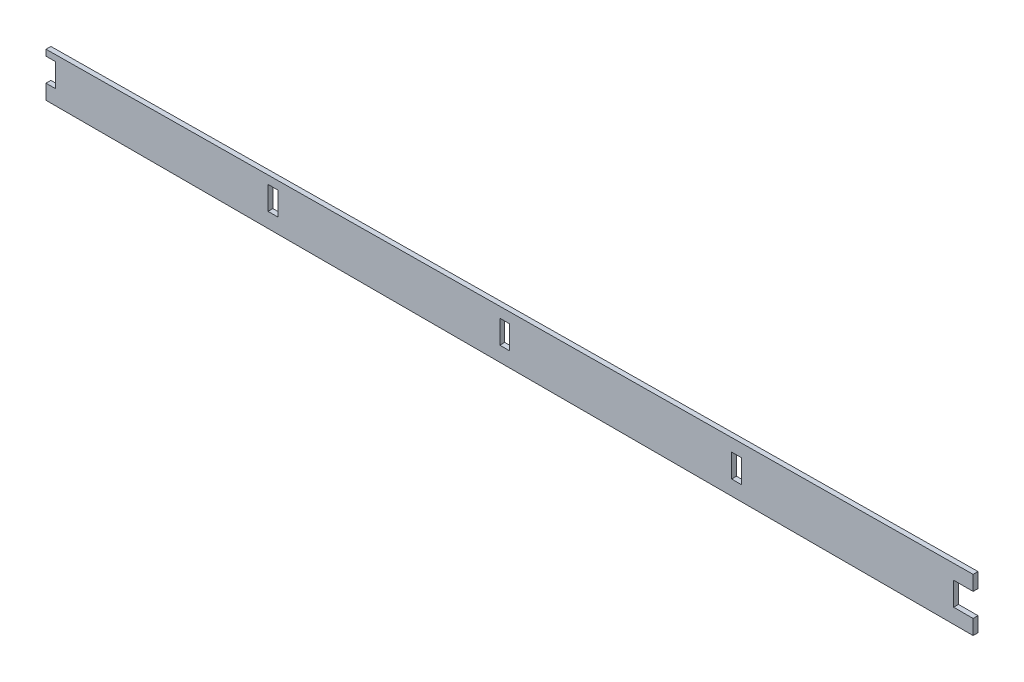
SolidWorks part; units mm, degrees
material "Balsa"
ref_plane "Front Plane" through (0, 0, 0) normal (0, 0, 1) x (1, 0, 0)
ref_plane "Top Plane" through (0, 0, 0) normal (0, 1, 0) x (1, 0, 0)
ref_plane "Right Plane" through (0, 0, 0) normal (1, 0, 0) x (0, 0, -1)
sketch "Sketch1" plane through (0, 0, 0) normal (0, 0, 1) x (1, 0, 0)
  line L0 (88.3257, 32.6276) -> (81.9757, 32.6276)
  line L1 (81.9757, 32.6276) -> (81.9757, 25.0076)
  line L2 (81.9757, 25.0076) -> (88.3257, 25.0076)
  line L3 (88.3257, 25.0076) -> (88.3257, 20.1687)
  line L4 (88.3257, 20.1687) -> (-213.9343, 20.1687)
  line L5 (-213.9343, 20.1687) -> (-213.9343, 25.0076)
  line L6 (-213.9343, 25.0076) -> (-210.7593, 25.0076)
  line L7 (-210.7593, 25.0076) -> (-210.7593, 32.6276)
  line L8 (-210.7593, 32.6276) -> (-213.9343, 32.6276)
  line L9 (-213.9343, 32.6276) -> (-213.9343, 34.5959)
  line L10 (-213.9343, 34.5959) -> (-210.7593, 34.6261) construction
  line L11 (-213.9343, 34.5959) -> (88.3257, 37.4665)
  line L12 (88.3257, 37.4665) -> (88.3257, 32.6276)
  line L13 (-138.3693, 25.0076) -> (-141.5443, 25.0076)
  line L14 (-141.5443, 25.0076) -> (-141.5443, 32.6276)
  line L15 (-141.5443, 32.6276) -> (-138.3693, 32.6276)
  line L16 (-138.3693, 32.6276) -> (-138.3693, 25.0076)
  line L17 (-62.8043, 32.6276) -> (-65.9793, 32.6276)
  line L18 (-65.9793, 32.6276) -> (-65.9793, 25.0076)
  line L19 (-65.9793, 25.0076) -> (-62.8043, 25.0076)
  line L20 (-62.8043, 25.0076) -> (-62.8043, 32.6276)
  line L21 (12.7607, 32.6276) -> (12.7607, 25.0076)
  line L22 (12.7607, 25.0076) -> (9.5857, 25.0076)
  line L23 (9.5857, 25.0076) -> (9.5857, 32.6276)
  line L24 (9.5857, 32.6276) -> (12.7607, 32.6276)
extrude "Boss-Extrude1" add sketch "Sketch1" along normal blind 1.5875
